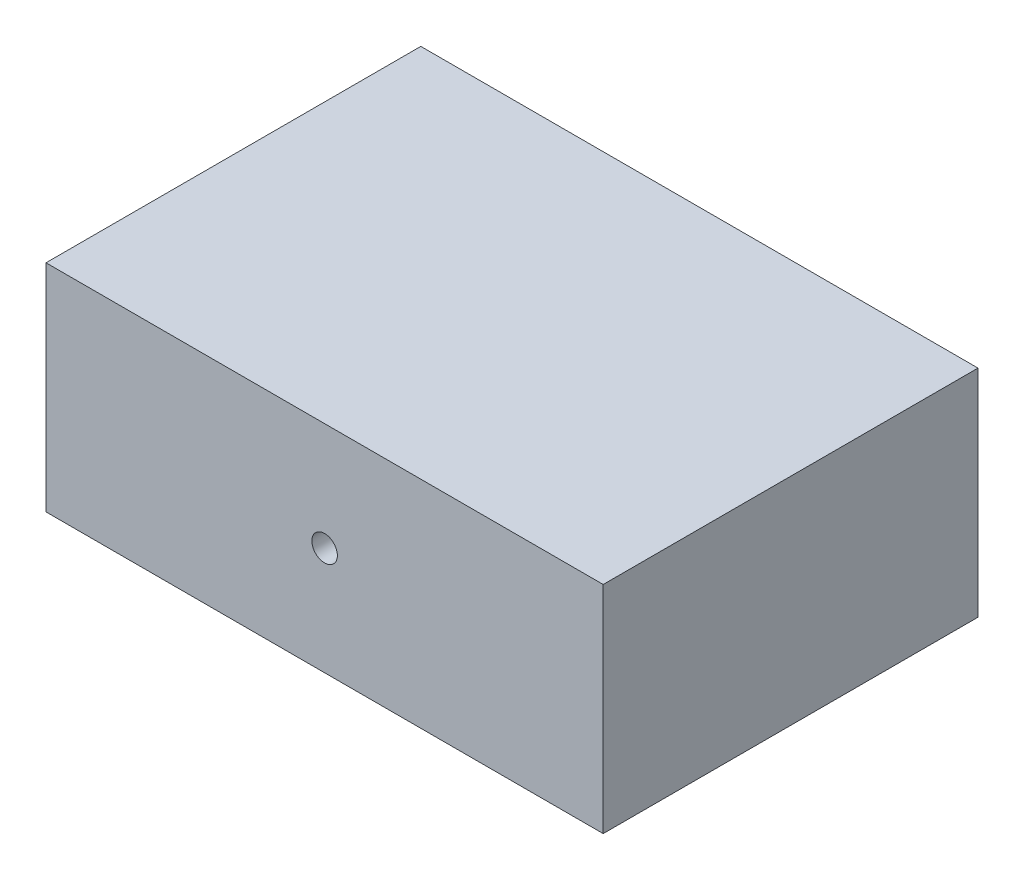
SolidWorks part; units mm, degrees
ref_plane "Front Plane" through (0, 0, 0) normal (0, 0, 1) x (1, 0, 0)
ref_plane "Top Plane" through (0, 0, 0) normal (0, 1, 0) x (1, 0, 0)
ref_plane "Right Plane" through (0, 0, 0) normal (1, 0, 0) x (0, 0, -1)
sketch "Sketch1" plane through (0, 0, 0) normal (0, 1, 0) x (1, 0, 0)
  line L1 (0, 0) -> (111.506, 0)
  line L2 (0, 0) -> (0, 75.0062)
  line L3 (0, 75.0062) -> (111.506, 75.0062)
  line L4 (111.506, 0) -> (111.506, 75.0062)
  dimension "D1" = 111.506
  dimension "D2" = 75.0062
extrude "Boss-Extrude1" add sketch "Sketch1" along normal blind 43.18
sketch "Sketch2" plane through (0, 0, 0) normal (0, 0, 1) x (1, 0, 0)
  line L0 (0, 43.18) -> (111.506, 43.18) construction
  line L2 (0, 43.18) -> (0, 0) construction
  circle A0 centre (55.753, 21.59) radius 3.175
  dimension "D3" = 6.35
  dimension "D1" = 21.59
  dimension "D2" = 55.753
hole_wizard "1/4-20 Tapped Hole1" positions "3DSketch2" profile "Sketch4" tap size "1/4-20" standard "ANSI Inch"
sketch3d "3DSketch2"
  point P0 (55.753, 21.59, 0)
sketch "Sketch4" plane through (55.753, 21.59, 0) normal (1, 0, 0) x (0, -1, 0)
  line L0 (0, 0) -> (0, 18.0438)
  line L1 (0, 18.0438) -> (2.5527, 16.51)
  line L2 (2.5527, 16.51) -> (2.5527, 0)
  line L5 (2.5527, 0) -> (0, 0)
  line L10 (0, 18.0438) -> (-2.5527, 16.51) construction
  line L11 (0, -6.35) -> (0, 107.95) construction
  dimension "Tap Drill Dia." = 5.1054
  dimension "Tap Drill Depth" = 16.51
  dimension "Drill Angle" = 118
cosmetic thread "Hole Thread1" parameters "D1"=12.7, "D2"=6.35
